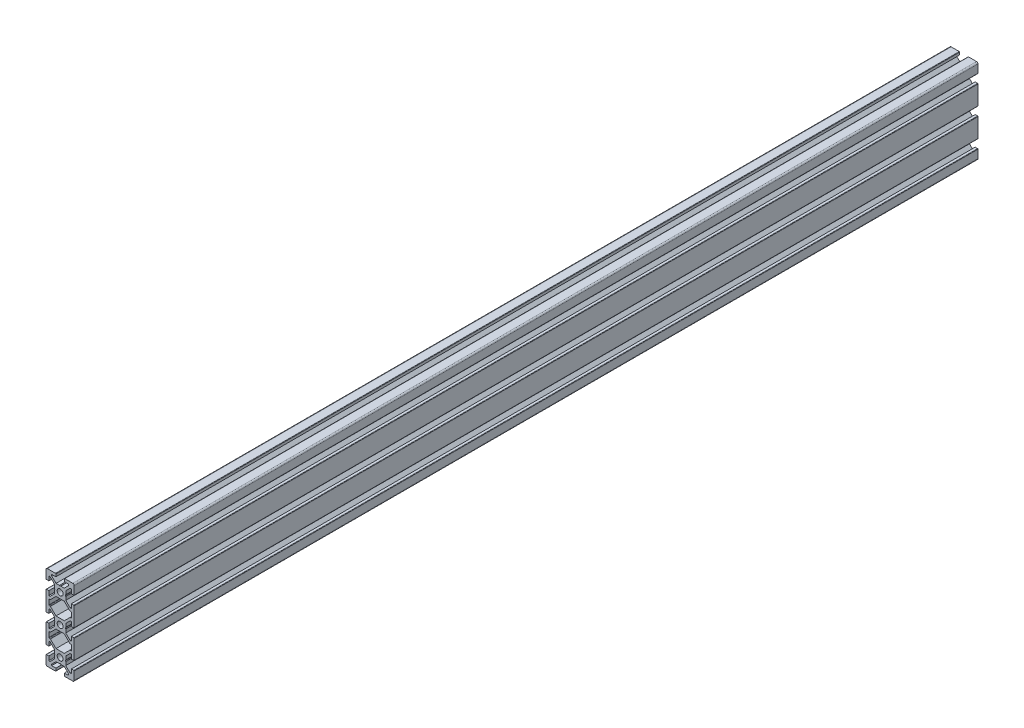
SolidWorks part; units mm, degrees
ref_plane "前基準面" through (0, 0, 0) normal (0, 0, 1) x (1, 0, 0)
ref_plane "上基準面" through (0, 0, 0) normal (0, 1, 0) x (1, 0, 0)
ref_plane "右基準面" through (0, 0, 0) normal (1, 0, 0) x (0, 0, -1)
ref_plane "平面1" through (0, 0, 0) normal (0, 0, 1) x (1, 0, 0)
sketch "草圖1" plane through (0, 0, 0) normal (0, 0, 1) x (1, 0, 0)
  line L0 (-10, 16.7) -> (-10, 3.3)
  line L1 (-9.7, 3) -> (-8, 3)
  line L2 (-8, 3) -> (-8, 6)
  line L3 (-8, 6) -> (-7.0607, 6)
  line L4 (-7.0607, 6) -> (-4, 2.9393)
  line L5 (-4, 2.9393) -> (-4, 0.5196)
  line L6 (-4, 0.5196) -> (-3.7, 0)
  line L7 (-3.7, 0) -> (-4, -0.5196)
  line L8 (-4, -0.5196) -> (-4, -2.9394)
  line L9 (-4, -2.9394) -> (-7.0606, -6)
  line L10 (-7.0606, -6) -> (-8, -6)
  line L11 (-8, -6) -> (-8, -3)
  line L12 (-8, -3) -> (-9.7, -3)
  line L13 (-10, -3.3) -> (-10, -16.7)
  line L14 (-9.7, -17) -> (-8, -17)
  line L15 (-8, -17) -> (-8, -14)
  line L16 (-8, -14) -> (-7.0607, -14)
  line L17 (-7.0607, -14) -> (-4, -17.0607)
  line L18 (-4, -17.0607) -> (-4, -19.4804)
  line L19 (-4, -19.4804) -> (-3.7, -20)
  line L20 (-3.7, -20) -> (-4, -20.5196)
  line L21 (-4, -20.5196) -> (-4, -22.9394)
  line L22 (-4, -22.9394) -> (-7.0606, -26)
  line L23 (-7.0606, -26) -> (-8, -26)
  line L24 (-8, -26) -> (-8, -23)
  line L25 (-8, -23) -> (-9.7, -23)
  line L26 (-10, -23.3) -> (-10, -29)
  line L27 (-9, -30) -> (-3.3, -30)
  line L28 (-3, -29.7) -> (-3, -28)
  line L29 (-3, -28) -> (-6, -28)
  line L30 (-6, -28) -> (-6, -27.0607)
  line L31 (-6, -27.0607) -> (-2.9393, -24)
  line L32 (-2.9393, -24) -> (-0.5191, -24)
  line L33 (-0.5191, -24) -> (0, -23.7)
  line L34 (0, -23.7) -> (0.5186, -24)
  line L35 (0.5186, -24) -> (2.9393, -24)
  line L36 (2.9393, -24) -> (6, -27.0607)
  line L37 (6, -27.0607) -> (6, -28)
  line L38 (6, -28) -> (3, -28)
  line L39 (3, -28) -> (3, -29.7)
  line L40 (3.3, -30) -> (9, -30)
  line L41 (10, -29) -> (10, -23.3)
  line L42 (9.7, -23) -> (8, -23)
  line L43 (8, -23) -> (8, -26)
  line L44 (8, -26) -> (7.0606, -26)
  line L45 (7.0606, -26) -> (4, -22.9394)
  line L46 (4, -22.9394) -> (4, -20.5196)
  line L47 (4, -20.5196) -> (3.7, -20)
  line L48 (3.7, -20) -> (4, -19.4804)
  line L49 (4, -19.4804) -> (4, -17.0607)
  line L50 (4, -17.0607) -> (7.0607, -14)
  line L51 (7.0607, -14) -> (8, -14)
  line L52 (8, -14) -> (8, -17)
  line L53 (8, -17) -> (9.7, -17)
  line L54 (10, -16.7) -> (10, -3.3)
  line L55 (9.7, -3) -> (8, -3)
  line L56 (8, -3) -> (8, -6)
  line L57 (8, -6) -> (7.0607, -6)
  line L58 (7.0607, -6) -> (4, -2.9393)
  line L59 (4, -2.9393) -> (4, -0.5196)
  line L60 (4, -0.5196) -> (3.7, 0)
  line L61 (3.7, 0) -> (4, 0.5196)
  line L62 (4, 0.5196) -> (4, 2.9393)
  line L63 (4, 2.9393) -> (7.0607, 6)
  line L64 (7.0607, 6) -> (8, 6)
  line L65 (8, 6) -> (8, 3)
  line L66 (8, 3) -> (9.7, 3)
  line L67 (10, 3.3) -> (10, 16.7)
  line L68 (9.7, 17) -> (8, 17)
  line L69 (8, 17) -> (8, 14)
  line L70 (8, 14) -> (7.0607, 14)
  line L71 (7.0607, 14) -> (4, 17.0607)
  line L72 (4, 17.0607) -> (4, 19.4804)
  line L73 (4, 19.4804) -> (3.7, 20)
  line L74 (3.7, 20) -> (4, 20.5196)
  line L75 (4, 20.5196) -> (4, 22.9394)
  line L76 (4, 22.9394) -> (7.0606, 26)
  line L77 (7.0606, 26) -> (8, 26)
  line L78 (8, 26) -> (8, 23)
  line L79 (8, 23) -> (9.7, 23)
  line L80 (10, 23.3) -> (10, 29)
  line L81 (9, 30) -> (3.3, 30)
  line L82 (3, 29.7) -> (3, 28)
  line L83 (3, 28) -> (6, 28)
  line L84 (6, 28) -> (6, 27.0607)
  line L85 (6, 27.0607) -> (2.9393, 24)
  line L86 (2.9393, 24) -> (0.5196, 24)
  line L87 (0.5196, 24) -> (0, 23.7)
  line L88 (0, 23.7) -> (-0.5196, 24)
  line L89 (-0.5196, 24) -> (-2.9393, 24)
  line L90 (-2.9393, 24) -> (-6, 27.0607)
  line L91 (-6, 27.0607) -> (-6, 28)
  line L92 (-6, 28) -> (-3, 28)
  line L93 (-3, 28) -> (-3, 29.7)
  line L94 (-3.3, 30) -> (-9, 30)
  line L95 (-10, 29) -> (-10, 23.3)
  line L96 (-9.7, 23) -> (-8, 23)
  line L97 (-8, 23) -> (-8, 26)
  line L98 (-8, 26) -> (-7.0606, 26)
  line L99 (-7.0606, 26) -> (-4, 22.9394)
  line L100 (-4, 22.9394) -> (-4, 20.5196)
  line L101 (-4, 20.5196) -> (-3.7, 20)
  line L102 (-3.7, 20) -> (-4, 19.4804)
  line L103 (-4, 19.4804) -> (-4, 17.0607)
  line L104 (-4, 17.0607) -> (-7.0607, 14)
  line L105 (-7.0607, 14) -> (-8, 14)
  line L106 (-8, 14) -> (-8, 17)
  line L107 (-8, 17) -> (-9.7, 17)
  line L108 (-7.7, 8) -> (-7.0636, 8)
  line L109 (-6.8515, 7.9121) -> (-2.9393, 4)
  line L110 (-2.9393, 4) -> (2.9393, 4)
  line L111 (2.9393, 4) -> (6.8515, 7.9121)
  line L112 (7.0636, 8) -> (7.7, 8)
  line L113 (8, 8.3) -> (8, 11.7)
  line L114 (7.7, 12) -> (7.0636, 12)
  line L115 (6.8515, 12.0879) -> (2.9393, 16)
  line L116 (2.9393, 16) -> (-2.9393, 16)
  line L117 (-2.9393, 16) -> (-6.8515, 12.0879)
  line L118 (-7.0636, 12) -> (-7.7, 12)
  line L119 (-8, 11.7) -> (-8, 8.3)
  line L120 (-8, -8.3) -> (-8, -11.7)
  line L121 (-7.7, -12) -> (-7.0636, -12)
  line L122 (-6.8515, -12.0879) -> (-2.9394, -16)
  line L123 (-2.9394, -16) -> (2.9393, -16)
  line L124 (2.9393, -16) -> (6.8515, -12.0879)
  line L125 (7.0636, -12) -> (7.7, -12)
  line L126 (8, -11.7) -> (8, -8.3)
  line L127 (7.7, -8) -> (7.0636, -8)
  line L128 (6.8515, -7.9121) -> (2.9393, -4)
  line L129 (2.9393, -4) -> (-2.9393, -4)
  line L130 (-2.9393, -4) -> (-6.8515, -7.9121)
  line L131 (-7.0636, -8) -> (-7.7, -8)
  arc A0 (-10, 3.3) -> (-9.7, 3) centre (-9.7, 3.3) ccw
  arc A1 (-9.7, -3) -> (-10, -3.3) centre (-9.7, -3.3) ccw
  arc A2 (-10, -16.7) -> (-9.7, -17) centre (-9.7, -16.7) ccw
  arc A3 (-9.7, -23) -> (-10, -23.3) centre (-9.7, -23.3) ccw
  arc A4 (-10, -29) -> (-9, -30) centre (-9, -29) ccw
  arc A5 (-3.3, -30) -> (-3, -29.7) centre (-3.3, -29.7) ccw
  arc A6 (3, -29.7) -> (3.3, -30) centre (3.3, -29.7) ccw
  arc A7 (9, -30) -> (10, -29) centre (9, -29) ccw
  arc A8 (10, -23.3) -> (9.7, -23) centre (9.7, -23.3) ccw
  arc A9 (9.7, -17) -> (10, -16.7) centre (9.7, -16.7) ccw
  arc A10 (10, -3.3) -> (9.7, -3) centre (9.7, -3.3) ccw
  arc A11 (9.7, 3) -> (10, 3.3) centre (9.7, 3.3) ccw
  arc A12 (10, 16.7) -> (9.7, 17) centre (9.7, 16.7) ccw
  arc A13 (9.7, 23) -> (10, 23.3) centre (9.7, 23.3) ccw
  arc A14 (10, 29) -> (9, 30) centre (9, 29) ccw
  arc A15 (3.3, 30) -> (3, 29.7) centre (3.3, 29.7) ccw
  arc A16 (-3, 29.7) -> (-3.3, 30) centre (-3.3, 29.7) ccw
  arc A17 (-9, 30) -> (-10, 29) centre (-9, 29) ccw
  arc A18 (-10, 23.3) -> (-9.7, 23) centre (-9.7, 23.3) ccw
  arc A19 (-9.7, 17) -> (-10, 16.7) centre (-9.7, 16.7) ccw
  circle A20 centre (0, 20) radius 2.1
  circle A21 centre (0, 0) radius 2.1
  circle A22 centre (0, -20) radius 2.1
  arc A23 (-8, 8.3) -> (-7.7, 8) centre (-7.7, 8.3) ccw
  arc A24 (-7.0636, 8) -> (-6.8515, 7.9121) centre (-7.0636, 7.7) cw
  arc A25 (6.8515, 7.9121) -> (7.0636, 8) centre (7.0636, 7.7) cw
  arc A26 (7.7, 8) -> (8, 8.3) centre (7.7, 8.3) ccw
  arc A27 (8, 11.7) -> (7.7, 12) centre (7.7, 11.7) ccw
  arc A28 (7.0636, 12) -> (6.8515, 12.0879) centre (7.0636, 12.3) cw
  arc A29 (-6.8515, 12.0879) -> (-7.0636, 12) centre (-7.0636, 12.3) cw
  arc A30 (-7.7, 12) -> (-8, 11.7) centre (-7.7, 11.7) ccw
  arc A31 (-8, -11.7) -> (-7.7, -12) centre (-7.7, -11.7) ccw
  arc A32 (-7.0636, -12) -> (-6.8515, -12.0879) centre (-7.0636, -12.3) cw
  arc A33 (6.8515, -12.0879) -> (7.0636, -12) centre (7.0636, -12.3) cw
  arc A34 (7.7, -12) -> (8, -11.7) centre (7.7, -11.7) ccw
  arc A35 (8, -8.3) -> (7.7, -8) centre (7.7, -8.3) ccw
  arc A36 (7.0636, -8) -> (6.8515, -7.9121) centre (7.0636, -7.7) cw
  arc A37 (-6.8515, -7.9121) -> (-7.0636, -8) centre (-7.0636, -7.7) cw
  arc A38 (-7.7, -8) -> (-8, -8.3) centre (-7.7, -8.3) ccw
extrude "填料-伸長1" add sketch "草圖1" against normal blind 640
